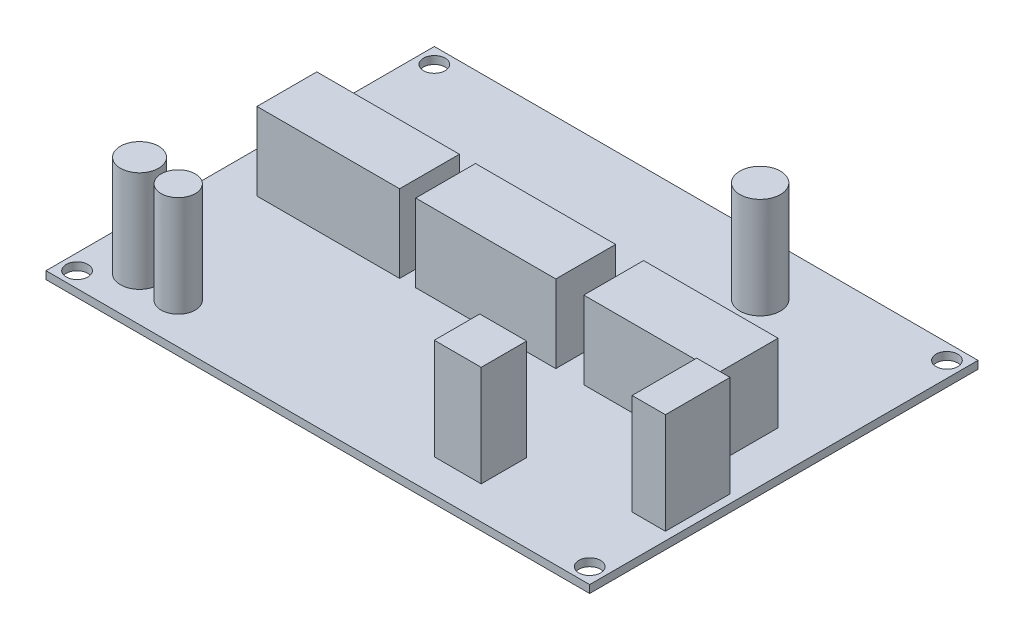
SolidWorks part; units mm, degrees
ref_plane "Front Plane" through (0, 0, 0) normal (0, 0, 1) x (1, 0, 0)
ref_plane "Top Plane" through (0, 0, 0) normal (0, 1, 0) x (1, 0, 0)
ref_plane "Right Plane" through (0, 0, 0) normal (1, 0, 0) x (0, 0, -1)
sketch "Sketch1" plane through (0, 0, 0) normal (0, 1, 0) x (1, 0, 0)
  line L1 (0, 0) -> (70, 0)
  line L2 (0, 0) -> (0, 50)
  line L3 (0, 50) -> (70, 50)
  line L4 (70, 0) -> (70, 50)
  dimension "D1" = 70
  dimension "D2" = 50
extrude "Boss-Extrude1" add sketch "Sketch1" along normal blind 1
sketch "Sketch2" plane through (0, 1, 0) normal (0, 1, 0) x (1, 0, 0)
  line L0 (2, 25) -> (0, 25) construction
  line L1 (2, 48) -> (68, 48) construction
  line L2 (2, 48) -> (2, 2) construction
  line L3 (2, 2) -> (68, 2) construction
  line L4 (68, 48) -> (68, 2) construction
  line L5 (0, 50) -> (0, 0) construction
  line L6 (35, 48) -> (35, 50) construction
  line L7 (70, 50) -> (0, 50) construction
  line L8 (35, 0) -> (35, 2) construction
  line L9 (0, 0) -> (70, 0) construction
  line L10 (68, 25) -> (70, 25) construction
  line L11 (70, 0) -> (70, 50) construction
  circle A0 centre (2, 48) radius 1.4
  circle A1 centre (68, 48) radius 1.4
  circle A2 centre (68, 2) radius 1.4
  circle A3 centre (2, 2) radius 1.4
  dimension "D3" = 2.8
  dimension "D1" = 2
  dimension "D2" = 2
extrude "Cut-Extrude1" cut sketch "Sketch2" against normal through all
sketch "Sketch3" plane through (0, 1, 0) normal (0, 1, 0) x (1, 0, 0)
  line L1 (5.2644, 21.8994) -> (23.6301, 21.8994)
  line L2 (5.2644, 21.8994) -> (5.2644, 29.6)
  line L3 (5.2644, 29.6) -> (23.6301, 29.6)
  line L4 (23.6301, 21.8994) -> (23.6301, 29.6)
  line L5 (25.7012, 21.8994) -> (43.7397, 21.8994)
  line L6 (25.7012, 21.8994) -> (25.7012, 29.6)
  line L7 (25.7012, 29.6) -> (43.7397, 29.6)
  line L8 (43.7397, 21.8994) -> (43.7397, 29.6)
  line L9 (47.3437, 21.8994) -> (64.6577, 21.8994)
  line L10 (47.3437, 21.8994) -> (47.3437, 29.6)
  line L11 (47.3437, 29.6) -> (64.6577, 29.6)
  line L12 (64.6577, 21.8994) -> (64.6577, 29.6)
extrude "Boss-Extrude2" add sketch "Sketch3" along normal blind 10
sketch "Sketch4" plane through (0, 1, 0) normal (0, 1, 0) x (1, 0, 0)
  line L1 (45.7517, 4.2426) -> (51.7908, 4.2426)
  line L2 (45.7517, 4.2426) -> (45.7517, 10.0979)
  line L3 (45.7517, 10.0979) -> (51.7908, 10.0979)
  line L4 (51.7908, 4.2426) -> (51.7908, 10.0979)
  line L5 (68.934, 10.8187) -> (64.6457, 10.8187)
  line L6 (68.934, 10.8187) -> (68.934, 19.1395)
  line L7 (68.934, 19.1395) -> (64.6457, 19.1395)
  line L8 (64.6457, 10.8187) -> (64.6457, 19.1395)
  circle A0 centre (11.8124, 5.2073) radius 2.1994
  circle A1 centre (49.1775, 42.7746) radius 2.6133
extrude "Boss-Extrude3" add sketch "Sketch4" along normal blind 13
sketch "Sketch5" plane through (0, 1, 0) normal (0, 1, 0) x (1, 0, 0)
  circle A0 centre (6.3673, 5.6766) radius 2.4615
  point P2 (6.3673, 5.6766)
extrude "Boss-Extrude4" add sketch "Sketch5" along normal blind 13
